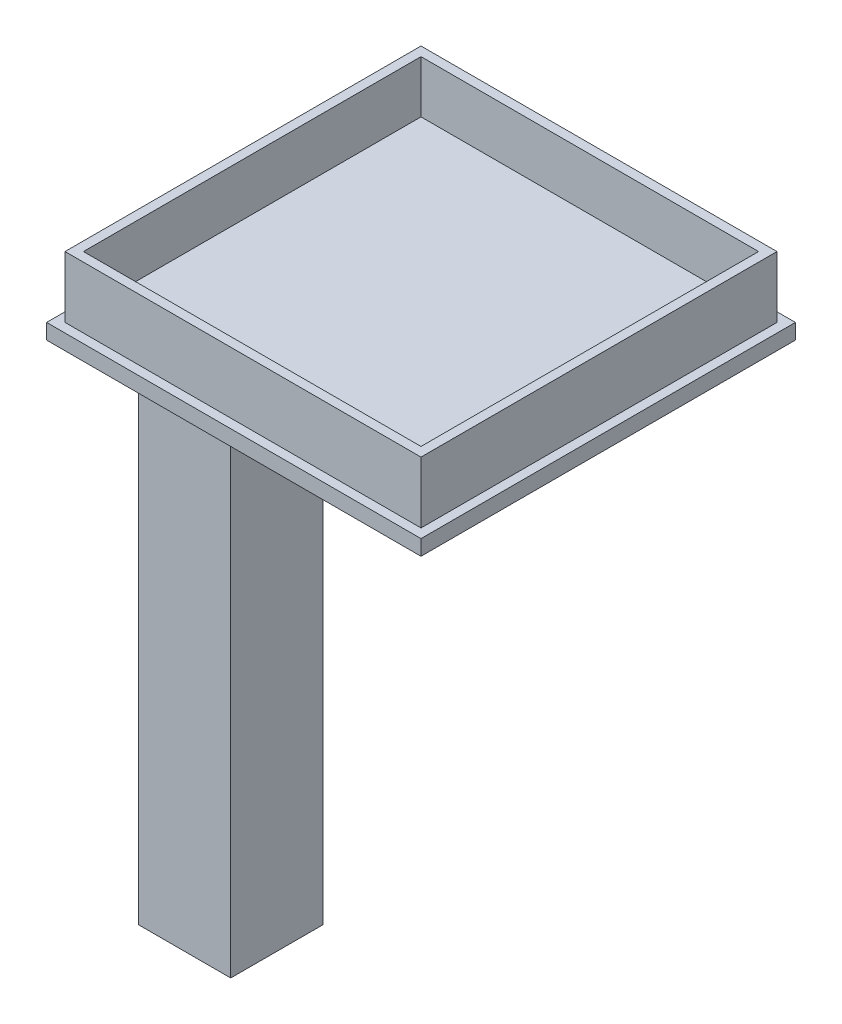
SolidWorks part; units mm, degrees
ref_plane "前视基准面" through (0, 0, 0) normal (0, 0, 1) x (1, 0, 0)
ref_plane "上视基准面" through (0, 0, 0) normal (0, 1, 0) x (1, 0, 0)
ref_plane "右视基准面" through (0, 0, 0) normal (1, 0, 0) x (0, 0, -1)
sketch "草图1" plane through (0, 0, 0) normal (0, 1, 0) x (1, 0, 0)
  line L1 (-58, 58) -> (58, 58)
  line L2 (-58, 58) -> (-58, -58)
  line L3 (-58, -58) -> (58, -58)
  line L4 (58, 58) -> (58, -58)
  point P4 (0, 58)
  point P6 (58, 0)
  dimension "D1" = 116
extrude "凸台-拉伸1" add sketch "草图1" along normal blind 20
shell "抽壳1" thickness 3
sketch "草图2" plane through (0, 0, 0) normal (0, -1, 0) x (1, 0, 0)
  line L0 (-61, 61) -> (-61, -61)
  line L1 (-61, -61) -> (61, -61)
  line L2 (61, -61) -> (61, 61)
  line L3 (61, 61) -> (-61, 61)
  line L4 (-58, 58) -> (-58, -58)
  line L5 (-58, -58) -> (58, -58)
  line L6 (58, -58) -> (58, 58)
  line L7 (58, 58) -> (-58, 58)
  line L8 (-58, 58) -> (-58, -58) construction
  line L9 (-58, -58) -> (58, -58) construction
  line L10 (58, -58) -> (58, 58) construction
  line L11 (58, 58) -> (-58, 58) construction
  dimension "D1" = 0
  dimension "D2" = 3
extrude "凸台-拉伸2" add sketch "草图2" along normal blind 5
sketch "草图4" plane through (0, -5, 0) normal (0, -1, 0) x (1, 0, 0)
  line L0 (-61, 61) -> (-61, -61) construction
  line L1 (-46, 46) -> (-16, 46)
  line L2 (-46, 46) -> (-46, 16)
  line L3 (-46, 16) -> (-16, 16)
  line L4 (-16, 46) -> (-16, 16)
  line L5 (61, 61) -> (-61, 61) construction
  line L6 (-44, 44) -> (-18, 44)
  line L7 (-18, 44) -> (-18, 18)
  line L8 (-44, 18) -> (-18, 18)
  line L9 (-44, 44) -> (-44, 18)
  dimension "D1" = 30
  dimension "D2" = 15
  dimension "D3" = 15
  dimension "D4" = 2
extrude "凸台-拉伸3" add sketch "草图4" along normal blind 165
